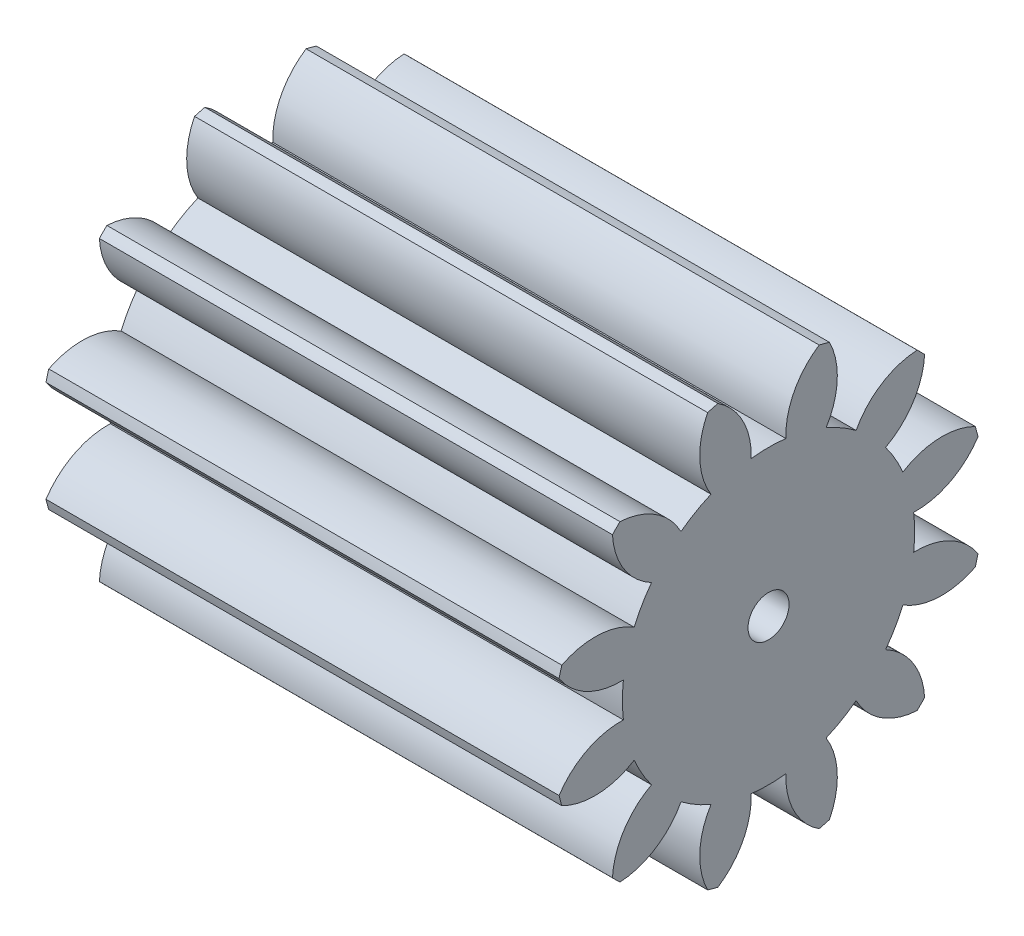
SolidWorks part; units mm, degrees
ref_plane "Plane1" through (0, 0, 0) normal (0, 0, 1) x (1, 0, 0)
ref_plane "Plane2" through (0, 0, 0) normal (0, 1, 0) x (1, 0, 0)
ref_plane "Plane3" through (0, 0, 0) normal (1, 0, 0) x (0, 0, -1)
other "Configuration Table"
sketch "HoldingSke" plane through (0, 0, 0) normal (0, 1, 0) x (1, 0, 0)
  line L0 (0, 0) -> (1.6302, -0.3465)
  line L1 (-15, 0) -> (100, 0) construction
  line L2 (0, 0) -> (-2.1039, 2.3779)
  line L3 (0, 0) -> (-11.863, 4.5341)
  line L4 (0, 0) -> (8.4473, 1.7955)
  line L5 (0, 0) -> (-46.8476, -17.4728)
  line L6 (0, 0) -> (-8.2896, -5.593)
  line L7 (-2.1039, 2.3779) -> (8.6586, 51.2059)
  line L8 (-76.2, 54.61) -> (-76.1, 54.61)
  line L9 (-71.009, 38.7566) -> (-53.1078, 45.2721)
  line L10 (-76.2, 71.12) -> (104.1128, 71.12)
  line L11 (0, 0) -> (-10, 0)
  line L12 (-76.2, 101.6) -> (-76.177, 101.6)
  line L13 (24.9733, 27.94) -> (52.9518, 28.4284)
  line L14 (24.9733, 27.94) -> (24.9743, 27.94)
  line L15 (24.9733, 27.94) -> (100.4006, 29.5858)
  line L16 (-63.627, -0.6) -> (-12.827, -0.6)
  circle A0 centre (0, 0) radius 0.4
  circle A1 centre (0, 0) radius 2.849
  circle A2 centre (0, 0) radius 37.5
  circle A3 centre (0, 0) radius 0.4
  dimension "MHD" = 5.698
  dimension "Hub_dia" = 75
  dimension "Bore" = 0.8
  dimension "MBD" = 0.8
  dimension "Num_teeth" = 12
  dimension "Pitch" = 1.6667
  dimension "Overall_len" = 50
  dimension "Show_teeth" = 12
  dimension "Thickness" = 10
  dimension "OAL" = 50.0001
  dimension "T_dim" = 0.1
  dimension "Ap" = 20
  dimension "H" = 19.05
  dimension "Pitch_radius" = 180.3128
  dimension "Width" = 10
  dimension "Backlash" = 0.023
  dimension "Addendum_fac" = 1
  dimension "Dedendum_fac" = 1.25
  dimension "Clearance_fac" = 0.25
  dimension "Dedendum_add" = 0.001
  dimension "Module" = 0.6
sketch "BasProSke" plane through (0, 0, 0) normal (0, 1, 0) x (1, 0, 0)
  line L0 (-10, 0) -> (60, 0) construction
  line L1 (0, 0) -> (0, 4.2)
  line L2 (0, 0) -> (10, 0)
  line L3 (10, 0) -> (10, 4.2)
  line L4 (10, 4.2) -> (0, 4.2)
  dimension "Thickness" = 10
  dimension "Diameter" = 8.4
revolve "Base-Revolve" add sketch "BasProSke" angle 360 about L0
sketch "TooCutSke" plane through (0, 0, 0) normal (1, 0, 0) x (0, 0, -1)
  line L1 (0, 0) -> (0, 107) construction
  line L2 (0, 0) -> (-0.5101, 3.5637) construction
  line L3 (0, 0) -> (-1.8502, 6.905) construction
  line L4 (-0.5101, 3.5637) -> (-0.9251, 3.4525) construction
  arc A0 (0.3376, 2.8289) -> (-0.3376, 2.8289) centre (0, 0) ccw
  arc A1 (1.0161, 4.1014) -> (-1.0161, 4.1014) centre (0, 0) ccw
  circle A2 centre (0, 0) radius 3.6 construction
  circle A3 centre (0, 0) radius 3.3829 construction
  arc A4 (-0.3376, 2.8289) -> (-1.0161, 4.1014) centre (-1.7768, 2.8787) ccw
  arc A5 (1.0161, 4.1014) -> (0.3376, 2.8289) centre (1.7768, 2.8787) ccw
  dimension "Root_dia" = 5.698
  dimension "Overcut_dia" = 8.4508
  dimension "Pitch_dia" = 7.2
  dimension "Base_dia" = 6.7658
  dimension "Flank_rad" = 1.44
  dimension "Half_ang" = 15
  dimension "Half_CT" = 0.4296
extrude "ToothCut" cut sketch "TooCutSke" along normal through all
fillet "Breaks" [suppressed] radius 0.012
fillet "RootFillets" [suppressed] radius 0.151
pattern_circular "TeethCuts" count 12 every 30 about axis through (-10, 0, 0) along (1, 0, 0) of "ToothCut", "RootFillets", "Breaks"
sketch "HubNeaOneSke" plane through (0, 0, 0) normal (-1, 0, 0) x (0, 0, 1)
  circle A0 centre (0, 0) radius 2.849
  dimension "Diameter" = 5.698
extrude "HubNearOne" [suppressed] add sketch "HubNeaOneSke" along normal blind 40.0001
sketch "HubNeaBotSke" plane through (0, 0, 0) normal (-1, 0, 0) x (0, 0, 1)
  circle A0 centre (0, 0) radius 2.849
  dimension "Diameter" = 5.698
extrude "HubNearBoth" [suppressed] add sketch "HubNeaBotSke" along normal blind 20
ref_plane "FarPln" through (10, 0, 0) normal (1, 0, 0) x (0, 0, -1)
sketch "HubFarSke" plane through (10, 0, 0) normal (1, 0, 0) x (0, 0, -1)
  circle A0 centre (0, 0) radius 2.849
  dimension "Diameter" = 5.698
extrude "HubFar" [suppressed] add sketch "HubFarSke" along normal blind 20
sketch "BorSke" plane through (0, 0, 0) normal (1, 0, 0) x (0, 0, -1)
  circle A0 centre (0, 0) radius 0.4
  dimension "Diameter" = 0.8
extrude "Bore" cut sketch "BorSke" along normal mid plane 100.0001
sketch "KeySke" plane through (0, 0, 0) normal (1, 0, 0) x (0, 0, -1)
  line L0 (-0.05, 0) -> (-0.05, 0.5)
  line L1 (-0.05, 0.5) -> (0.05, 0.5)
  line L2 (0.05, 0.5) -> (0.05, 0)
  line L3 (0, 0) -> (0, 34) construction
  line L4 (-0.05, 0) -> (0.05, 0)
  dimension "Offset" = 0.5
  dimension "Width" = 0.1
extrude "Keyway" [suppressed] cut sketch "KeySke" along normal mid plane 100.0001
pattern_circular "Keyway2" [suppressed] count 2 every 90 about axis through (-10, 0, 0) along (1, 0, 0)
equation "' \"Module@HoldingSke\" = 6.35"
equation "' \"Num_teeth@HoldingSke\" = 12"
equation "' \"Ap@HoldingSke\" =  20"
equation "' \"Ap@HoldingSke\" = 20"
equation "' \"Width@HoldingSke\" = 0.5 * 25.4"
equation "' \"Hub_dia@HoldingSke\"= 1 * 25.4"
equation "' \"Hub_dia@HoldingSke\" = 1 * 25.4"
equation "' \"Overall_len@HoldingSke\" = 1.0 * 25.4"
equation "' \"Bore@HoldingSke\" = 0.75 * 25.4"
equation "' \"T_dim@HoldingSke\" = 0.1 * 25.4"
equation "' \"Width@KeySke\" = 0.25 * 25.4"
equation "' \"Show_teeth@HoldingSke\" = 13"
equation "' \"Backlash@HoldingSke\" = 0.009 * 25.4"
equation "' \"Addendum_fac@HoldingSke\" = 1.0"
equation "' \"Dedendum_fac@HoldingSke\" = 1.25"
equation "' \"Dedendum_add@HoldingSke\" = 0.00005 * 25.4"
equation "' \"Clearance_fac@HoldingSke\" = 0.25"
equation "\"Pitch@HoldingSke\" = 1 / \"Module@HoldingSke\""
equation "\"Overcut_dia@TooCutSke\" = (\"Num_teeth@HoldingSke\" + 2 * \"Addendum_fac@HoldingSke\") / \"Pitch@HoldingSke\" + 0.002 * 25.4"
equation "\"Pitch_dia@TooCutSke\" = \"Num_teeth@HoldingSke\" / \"Pitch@HoldingSke\""
equation "\"Base_dia@TooCutSke\" = \"Num_teeth@HoldingSke\" / \"Pitch@HoldingSke\" * cos((\"Ap@HoldingSke\"  * 3.14159265 / 180))"
equation "\"Root_dia@TooCutSke\" = (\"Num_teeth@HoldingSke\" + 2) / \"Pitch@HoldingSke\" - 2 * (\"Addendum_fac@HoldingSke\" + \"Dedendum_fac@HoldingSke\") / \"Pitch@HoldingSke\" - \"Dedendum_add@HoldingSke\" * 2"
equation "\"Half_ang@TooCutSke\" = 180 / \"Num_teeth@HoldingSke\""
equation "\"Half_CT@TooCutSke\" = \"Num_teeth@HoldingSke\" / \"Pitch@HoldingSke\" * sin((3.14159265 / 2 / \"Num_teeth@HoldingSke\")) / 2 - 7 * \"Backlash@HoldingSke\" / 4"
equation "\"Flank_rad@TooCutSke\" = \"Num_teeth@HoldingSke\" / \"Pitch@HoldingSke\" / 5"
equation "\"Radius@RootFillets\" = \"Clearance_fac@HoldingSke\" / \"Pitch@HoldingSke\" + \"Dedendum_add@HoldingSke\""
equation "\"Break_rad@Breaks\" = 0.02 / \"Pitch@HoldingSke\""
equation "\"Thickness@HoldingSke\" = \"Width@HoldingSke\""
equation "\"OAL@HoldingSke\" = \"Thickness@HoldingSke\""
equation "\"MHD@HoldingSke\" = (\"Num_teeth@HoldingSke\" + 2) / \"Pitch@HoldingSke\" - 2 * (\"Addendum_fac@HoldingSke\" + \"Dedendum_fac@HoldingSke\")  / \"Pitch@HoldingSke\" - \"Dedendum_add@HoldingSke\" * 2"
equation "\"MBD@HoldingSke\" = (\"Num_teeth@HoldingSke\" + 2) / \"Pitch@HoldingSke\" - 2 * (\"Addendum_fac@HoldingSke\" + \"Dedendum_fac@HoldingSke\")  / \"Pitch@HoldingSke\" - \"Dedendum_add@HoldingSke\" * 2 - 0.002 * 25.4"
equation "\"MHD@HoldingSke\" = ((sgn( \"MHD@HoldingSke\" - \"Hub_dia@HoldingSke\" )-1)*( \"MHD@HoldingSke\" - \"Hub_dia@HoldingSke\" ))/-2+ \"Hub_dia@HoldingSke\""
equation "\"MBD@HoldingSke\" = ((sgn( \"MBD@HoldingSke\" - \"Bore@HoldingSke\" )-1)*( \"MBD@HoldingSke\" - \"Bore@HoldingSke\" ))/-2+ \"Bore@HoldingSke\""
equation "\"OAL@HoldingSke\" = ((sgn( \"OAL@HoldingSke\" - \"Overall_len@HoldingSke\" )+1)*( \"OAL@HoldingSke\" - \"Overall_len@HoldingSke\" ))/2 + \"Overall_len@HoldingSke\" + 0.000002 * 25.4"
equation "\"Num_teeth@TeethCuts\" = int( \"Show_teeth@HoldingSke\" ) + 1"
equation "\"Num_teeth@TeethCuts\" = ((sgn( \"Num_teeth@TeethCuts\" - \"Num_teeth@HoldingSke\" )-1)*( \"Num_teeth@TeethCuts\" - \"Num_teeth@HoldingSke\" ))/-2+ \"Num_teeth@HoldingSke\""
equation "\"Num_teeth@TeethCuts\" = ((sgn( \"Num_teeth@TeethCuts\" - 2.0)+1)*( \"Num_teeth@TeethCuts\" - 2.0))/2 +2.0"
equation "\"Angle@TeethCuts\" = 360.0 / \"Num_teeth@HoldingSke\""
equation "\"Diameter@BasProSke\" = (\"Num_teeth@HoldingSke\" + 2 * \"Addendum_fac@HoldingSke\") / \"Pitch@HoldingSke\""
equation "\"Thickness@BasProSke\"  = \"Thickness@HoldingSke\""
equation "' \"Fillet_rad@BasProSke\" =  \"Thickness@HoldingSke\" * 0.05"
equation "' \"Fillet_rad@BasProSke\" = \"Thickness@HoldingSke\" * 0.05"
equation "\"MHD@HoldingSke\" = ((sgn( \"MHD@HoldingSke\" - \"Root_dia@TooCutSke\" )-1)*( \"MHD@HoldingSke\" - \"Root_dia@TooCutSke\" ))/-2+ \"Root_dia@TooCutSke\""
equation "\"Diameter@HubNeaOneSke\" = \"MHD@HoldingSke\""
equation "\"Length@HubNearOne\" = \"OAL@HoldingSke\" - \"Thickness@BasProSke\""
equation "\"Diameter@HubNeaBotSke\" = \"MHD@HoldingSke\""
equation "\"Length@HubNearBoth\" = ( \"OAL@HoldingSke\" - \"Thickness@BasProSke\" ) / 2.0"
equation "\"Thickness@FarPln\" = \"Thickness@BasProSke\""
equation "\"Diameter@HubFarSke\" = \"MHD@HoldingSke\""
equation "\"Length@HubFar\" = ( \"OAL@HoldingSke\" - \"Thickness@BasProSke\" ) / 2.0"
equation "\"Diameter@BorSke\" = \"MBD@HoldingSke\""
equation "\"D1@Bore\" = \"OAL@HoldingSke\" * 2.0"
equation "\"D1@Keyway\" = \"OAL@HoldingSke\" * 2.0"
equation "\"Offset@KeySke\" = \"T_dim@HoldingSke\" + \"MBD@HoldingSke\" / 2.0"
